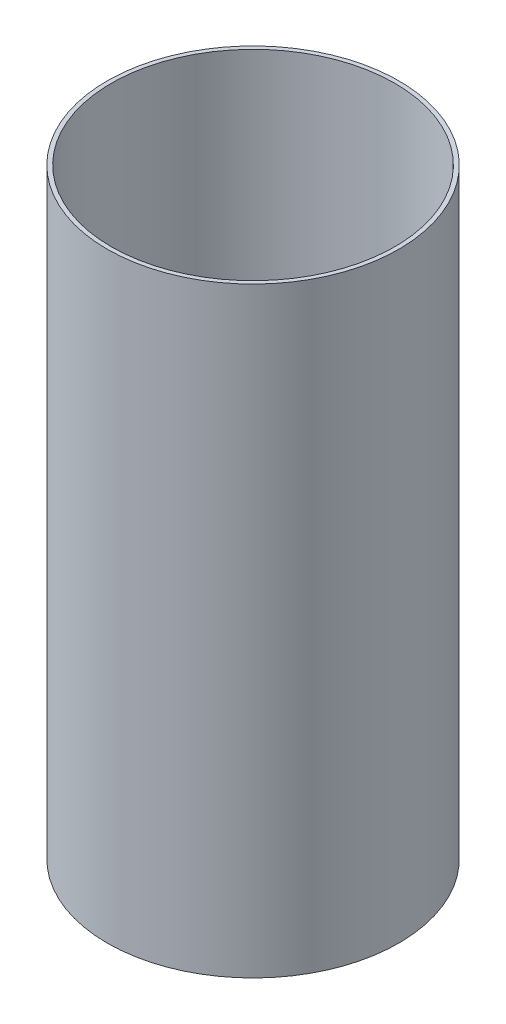
SolidWorks part; units mm, degrees
ref_plane "Front Plane" through (0, 0, 0) normal (0, 0, 1) x (1, 0, 0)
ref_plane "Top Plane" through (0, 0, 0) normal (0, 1, 0) x (1, 0, 0)
ref_plane "Right Plane" through (0, 0, 0) normal (1, 0, 0) x (0, 0, -1)
sketch "Sketch1" plane through (0, 0, 0) normal (0, 1, 0) x (1, 0, 0)
  circle A0 centre (0, 0) radius 76.2
  circle A1 centre (0, 0) radius 74.04
  dimension "D1" = 152.4
  dimension "D2" = 2.16
extrude "Boss-Extrude1" add sketch "Sketch1" along normal blind 314
